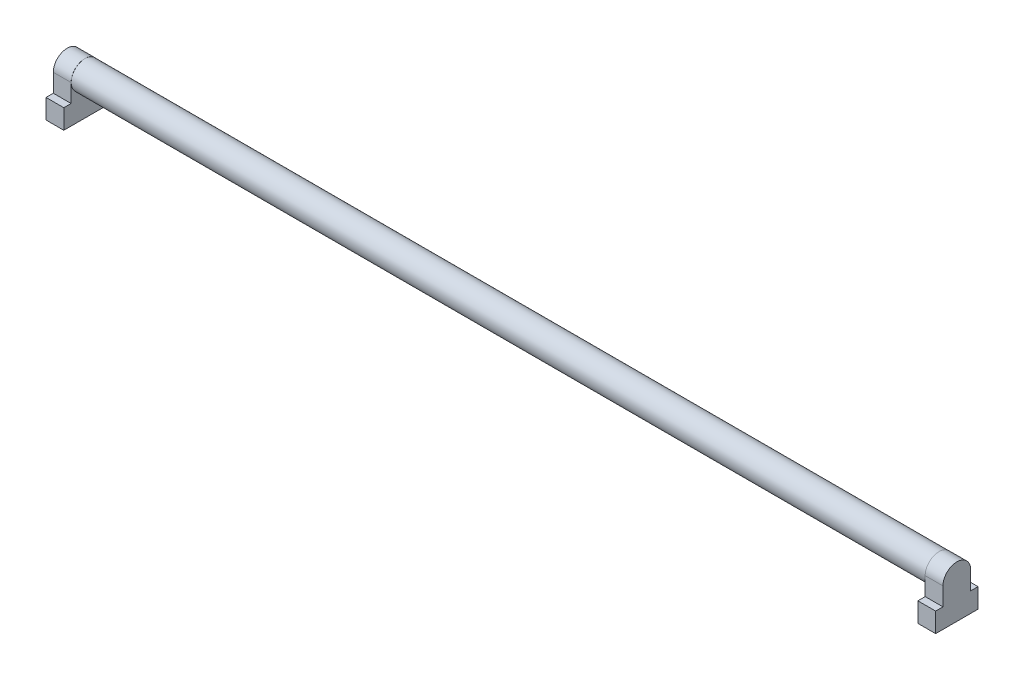
SolidWorks part; units mm, degrees
ref_plane "Front Plane" through (0, 0, 0) normal (0, 0, 1) x (1, 0, 0)
ref_plane "Top Plane" through (0, 0, 0) normal (0, 1, 0) x (1, 0, 0)
ref_plane "Right Plane" through (0, 0, 0) normal (1, 0, 0) x (0, 0, -1)
sketch "Sketch1" plane through (0, 0, 0) normal (1, 0, 0) x (0, 0, -1)
  circle A0 centre (0, 0) radius 7.75
  dimension "D1" = 15.5
extrude "Boss-Extrude1" add sketch "Sketch1" along normal blind 240
sketch "Sketch2" plane through (240, 0, 0) normal (1, 0, 0) x (0, 0, -1)
  line L0 (-7.8, 0) -> (-7.8, -10.2)
  line L1 (-7.8, -10.2) -> (-11.9, -10.2)
  line L2 (-11.9, -10.2) -> (-11.9, -21.2)
  line L3 (-11.9, -21.2) -> (11.9, -21.2)
  line L4 (11.9, -21.2) -> (11.9, -10.2)
  line L5 (11.9, -10.2) -> (7.8, -10.2)
  line L6 (7.8, -10.2) -> (7.8, 0)
  arc A4 (-7.8, 0) -> (7.8, 0) centre (0, 0) cw
  point P3 (0, 0)
  point P5 (0, 0)
  dimension "D1" = 23.8
  dimension "D4" = 7.8
  dimension "D2" = 10.2
  dimension "D3" = 11
extrude "Boss-Extrude2" add sketch "Sketch2" along normal blind 10
ref_plane "Plane1" through (0, 0, 0) normal (-1, 0, 0) x (0, 0, 1)
mirror "Mirror1" about plane through (0, 0, 0) normal (-1, 0, 0) of "Boss-Extrude2", "Boss-Extrude1"
